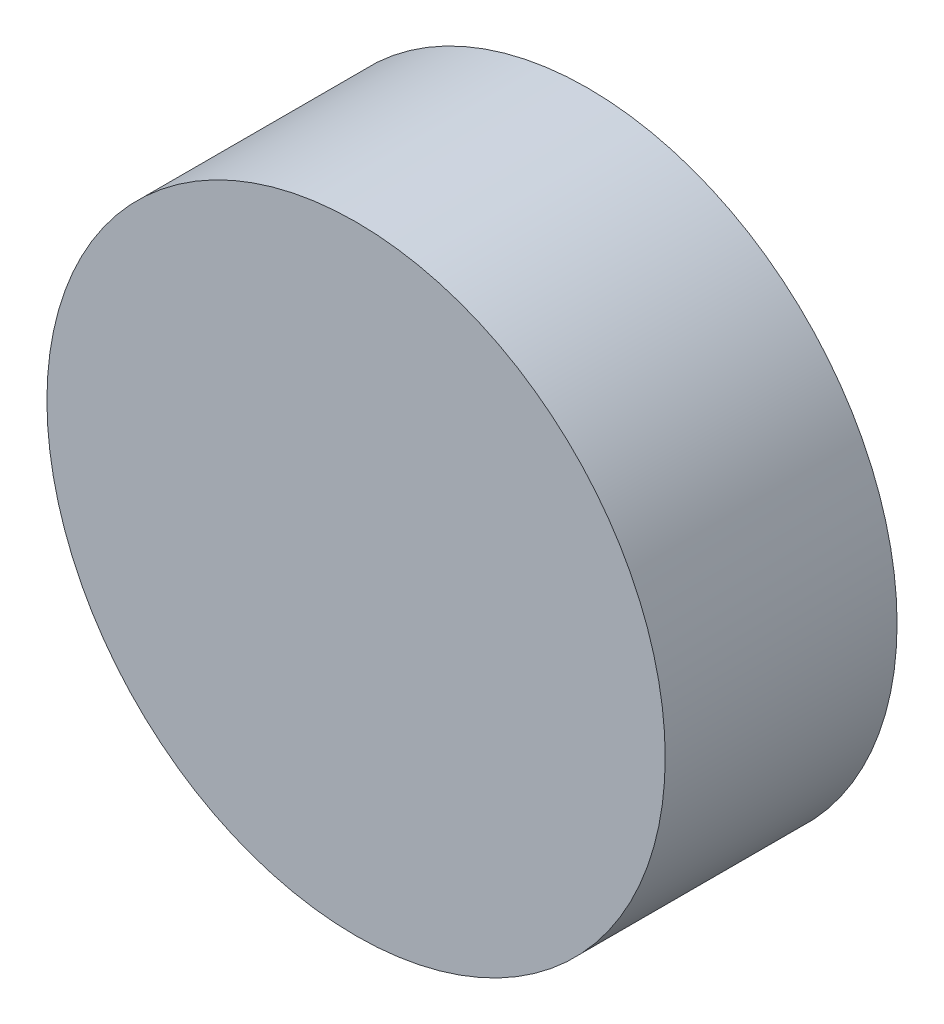
SolidWorks part; units mm, degrees
material "ABS"
ref_plane "Front Plane" through (0, 0, 0) normal (0, 0, 1) x (1, 0, 0)
ref_plane "Top Plane" through (0, 0, 0) normal (0, 1, 0) x (1, 0, 0)
ref_plane "Right Plane" through (0, 0, 0) normal (1, 0, 0) x (0, 0, -1)
sketch "Sketch1" plane through (0, 0, 0) normal (0, 0, 1) x (1, 0, 0)
  circle A0 centre (0, 0) radius 5.08
  dimension "D1" = 10.16
extrude "Boss-Extrude1" add sketch "Sketch1" along normal blind 3.81
